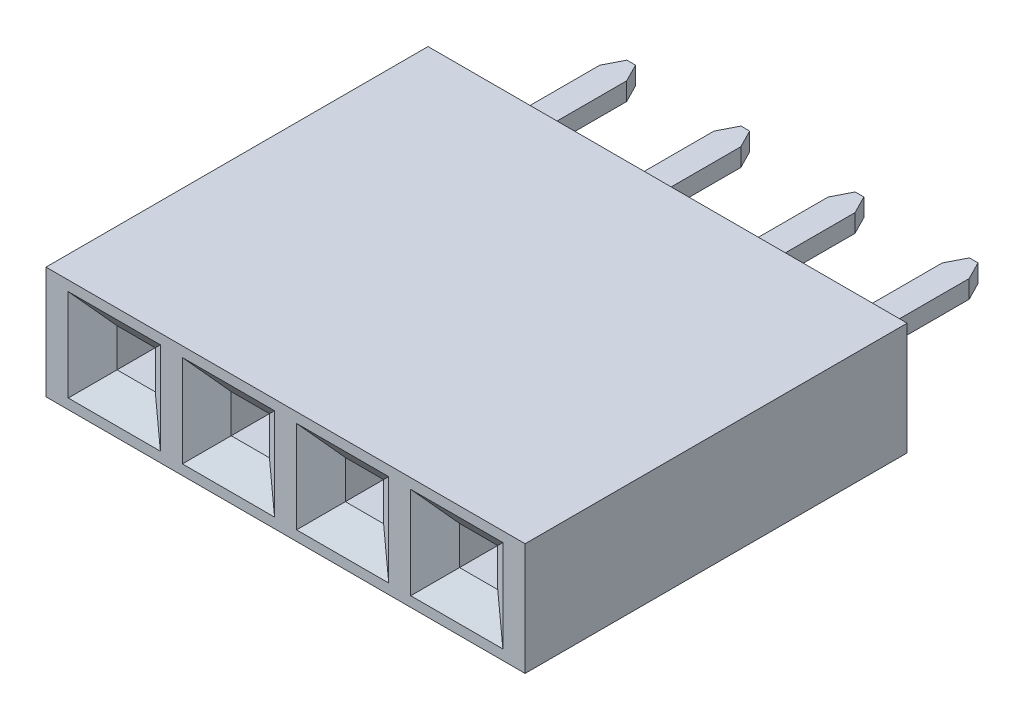
SolidWorks part; units mm, degrees
other "Детальный элемент1"
ref_plane "Спереди" through (0, 0, 0) normal (0, 0, 1) x (1, 0, 0)
ref_plane "Сверху" through (0, 0, 0) normal (0, 1, 0) x (1, 0, 0)
ref_plane "Справа" through (0, 0, 0) normal (1, 0, 0) x (0, 0, -1)
sketch "Эскиз1" plane through (0, 0, 0) normal (0, 0, 1) x (1, 0, 0)
  line L1 (-5.33, -1.25) -> (5.33, -1.25)
  line L2 (-5.33, -1.25) -> (-5.33, 1.25)
  line L3 (-5.33, 1.25) -> (5.33, 1.25)
  line L4 (5.33, -1.25) -> (5.33, 1.25)
  line L5 (-5.33, -1.25) -> (5.33, 1.25) construction
  line L6 (-5.33, 1.25) -> (5.33, -1.25) construction
  point P0 (0, 0)
  dimension "D1" = 2.5
  dimension "D2" = 10.66
extrude "Бобышка-Вытянуть1" add sketch "Эскиз1" along normal blind 8.5
sketch "Эскиз2" plane through (0, 0, 8.5) normal (0, 0, 1) x (1, 0, 0)
  line L0 (5.33, -1.25) -> (5.33, 1.25) construction
  line L1 (3.385, 0.425) -> (4.235, 0.425)
  line L2 (3.385, 0.425) -> (3.385, -0.425)
  line L3 (3.385, -0.425) -> (4.235, -0.425)
  line L4 (4.235, 0.425) -> (4.235, -0.425)
  line L5 (3.385, 0.425) -> (4.235, -0.425) construction
  line L6 (3.385, -0.425) -> (4.235, 0.425) construction
  point P0 (3.81, 0)
  point P5 (0, 0)
  point P9 (0, 0)
  dimension "D1" = 1.52
  dimension "D2" = 0.85
extrude "Вырез-Вытянуть1" cut sketch "Эскиз2" against normal blind 6
chamfer "Фаска1" distance 0.6 angle 39 4 edges at (4.235, 0, 8.5) (3.81, -0.425, 8.5) (3.81, 0.425, 8.5) (3.385, 0, 8.5)
pattern_linear "Линейный массив1" count 4 spacing 2.54 along (-1, 0, 0) of "Фаска1", "Вырез-Вытянуть1"
sketch "Эскиз3" plane through (0, 0, 0) normal (0, 0, -1) x (-1, 0, 0)
  line L1 (-3.51, -0.2) -> (-4.11, -0.2)
  line L2 (-3.51, -0.2) -> (-3.51, 0.2)
  line L3 (-3.51, 0.2) -> (-4.11, 0.2)
  line L4 (-4.11, -0.2) -> (-4.11, 0.2)
  line L5 (-3.51, -0.2) -> (-4.11, 0.2) construction
  line L6 (-3.51, 0.2) -> (-4.11, -0.2) construction
  point P0 (-3.81, 0)
  point P5 (0, 0)
  dimension "D1" = 0.6
  dimension "D2" = 0.4
extrude "Бобышка-Вытянуть2" add sketch "Эскиз3" along normal blind 3 separate body
chamfer "Фаска2" distance 0.4 angle 27 2 edges at (3.51, 0, -3) (4.11, 0, -3)
pattern_linear "Линейный массив2" count 4 spacing 2.54 along (-1, 0, 0) of bodies 110
equation "\"N\" = 4"
equation "\"D2@Эскиз1\"=\"N\"*2.54+0.5"
equation "\"D1@Эскиз2\"=(2.54+0.5)/2"
equation "\"D1@Линейный массив1\"=\"N\""
equation "\"D1@Линейный массив2\"=\"N\""
